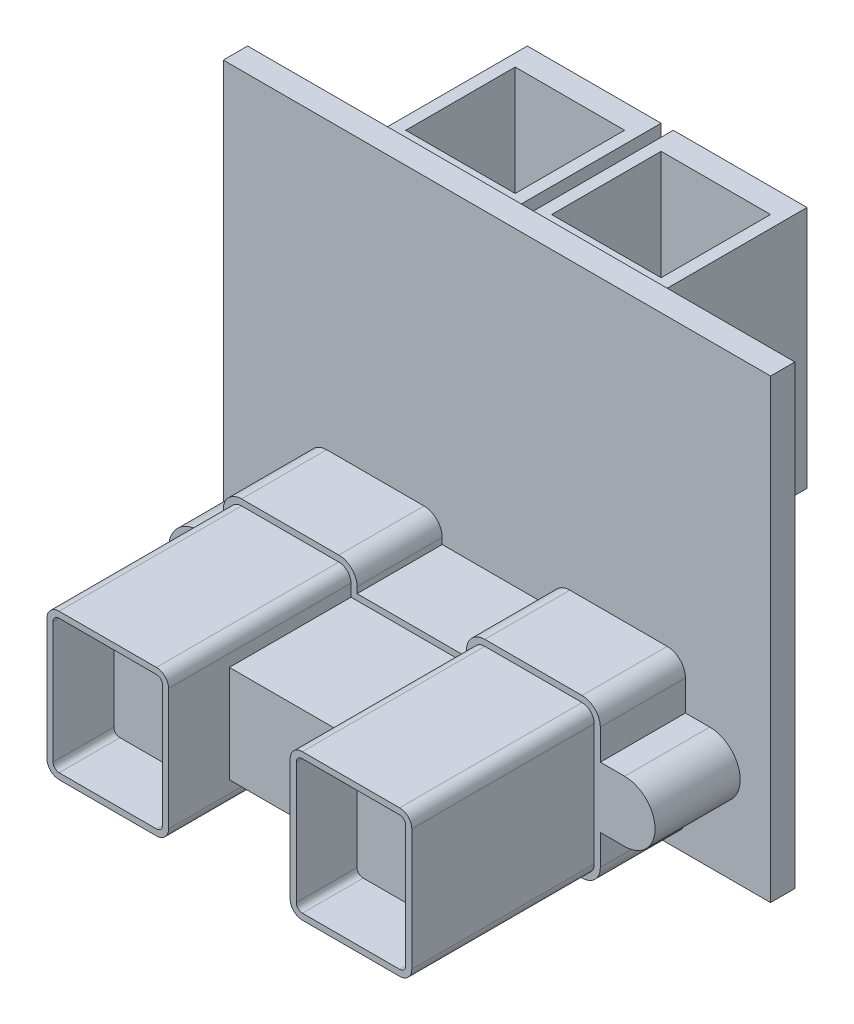
SolidWorks part; units mm, degrees
ref_plane "Front Plane" through (0, 0, 0) normal (0, 0, 1) x (1, 0, 0)
ref_plane "Top Plane" through (0, 0, 0) normal (0, 1, 0) x (1, 0, 0)
ref_plane "Right Plane" through (0, 0, 0) normal (1, 0, 0) x (0, 0, -1)
sketch "Sketch1" plane through (0, 0, 0) normal (0, 0, 1) x (1, 0, 0)
  line L1 (-22.5, 18.75) -> (22.5, 18.75)
  line L2 (-22.5, 18.75) -> (-22.5, -18.75)
  line L3 (-22.5, -18.75) -> (22.5, -18.75)
  line L4 (22.5, 18.75) -> (22.5, -18.75)
  line L5 (-22.5, 18.75) -> (22.5, -18.75) construction
  line L6 (-22.5, -18.75) -> (22.5, 18.75) construction
  point P0 (0, 0)
  dimension "D1" = 37.5
  dimension "D2" = 45
extrude "Boss-Extrude1" add sketch "Sketch1" along normal blind 2
sketch "Sketch2" plane through (0, 0, 2) normal (0, 0, 1) x (1, 0, 0)
  line L0 (0, 18.75) -> (0, -18.75) construction
  line L1 (22.5, 18.75) -> (-22.5, 18.75) construction
  line L2 (-22.5, -18.75) -> (22.5, -18.75) construction
  line L4 (-20, -4.75) -> (20, -4.75)
  line L5 (-20, -4.75) -> (-20, -17.75)
  line L6 (-20, -17.75) -> (20, -17.75)
  line L7 (20, -4.75) -> (20, -17.75)
  line L8 (-20, -4.75) -> (20, -17.75) construction
  line L9 (-20, -17.75) -> (20, -4.75) construction
  point P6 (0, -11.25)
  point P11 (0, -10.9554)
  dimension "D1" = 13
  dimension "D2" = 40
  dimension "D3" = 1
extrude "Boss-Extrude2" add sketch "Sketch2" along normal blind 7
sketch "Sketch3" plane through (0, 0, 9) normal (0, 0, 1) x (1, 0, 0)
  line L0 (0, -4.75) -> (0, -17.75) construction
  line L1 (20, -4.75) -> (-20, -4.75) construction
  line L2 (-20, -17.75) -> (20, -17.75) construction
  line L3 (-5, -7.25) -> (-5, -5.25)
  line L4 (5, -5.25) -> (15, -5.25)
  line L5 (5, -7.25) -> (5, -5.25)
  line L6 (5, -17.25) -> (15, -17.25)
  line L7 (15, -5.25) -> (15, -17.25)
  line L8 (-5, -5.25) -> (-15, -5.25)
  line L9 (5, -15.25) -> (5, -17.25)
  line L10 (-5, -17.25) -> (-15, -17.25)
  line L11 (-15, -5.25) -> (-15, -17.25)
  line L12 (5, -7.25) -> (-5, -7.25)
  line L13 (-5, -15.25) -> (-5, -17.25)
  line L14 (5, -15.25) -> (-5, -15.25)
  line L15 (-20, -17.75) -> (20, -17.75) construction
  point P20 (0, -7.25)
  point P24 (0, -15.25)
  dimension "D1" = 0.5
  dimension "D2" = 0.5
  dimension "D3" = 30
  dimension "D5" = 10
  dimension "D6" = 2
  dimension "D7" = 2
extrude "Boss-Extrude3" add sketch "Sketch3" along normal blind 15
fillet "Fillet1" radius 1 8 edges at (-15, -17.25, 16.5) (-5, -17.25, 16.5) (5, -17.25, 16.5) (-15, -5.25, 16.5) (15, -17.25, 16.5) (15, -5.25, 16.5) (5, -5.25, 16.5) (-5, -5.25, 16.5)
sketch "Sketch4" plane through (0, 0, 24) normal (0, 0, 1) x (1, 0, 0)
  line L0 (-5.5, -14.75) -> (-5.5, -7.75)
  line L1 (5.5, -7.75) -> (5.5, -14.75)
  line L2 (5, -7.25) -> (5, -15.25)
  line L3 (5, -15.25) -> (-5, -15.25)
  line L4 (-5, -15.25) -> (-5, -7.25)
  line L5 (-5, -7.25) -> (5, -7.25)
  line L48 (-14.5, -6.25) -> (-14.5, -16.25)
  line L49 (-14, -16.75) -> (-6, -16.75)
  line L50 (-5.5, -16.25) -> (-5.5, -14.75)
  line L51 (-5.5, -14.75) -> (5.5, -14.75)
  line L52 (5.5, -14.75) -> (5.5, -16.25)
  line L53 (6, -16.75) -> (14, -16.75)
  line L54 (14.5, -16.25) -> (14.5, -6.25)
  line L55 (14, -5.75) -> (6, -5.75)
  line L56 (5.5, -6.25) -> (5.5, -7.75)
  line L57 (5.5, -7.75) -> (-5.5, -7.75)
  line L58 (-5.5, -7.75) -> (-5.5, -6.25)
  line L59 (-6, -5.75) -> (-14, -5.75)
  line L60 (-14.5, -6.25) -> (-14.5, -16.25)
  line L61 (-14, -16.75) -> (-6, -16.75)
  line L62 (-5.5, -16.25) -> (-5.5, -14.75)
  line L63 (-5.5, -14.75) -> (5.5, -14.75) construction
  line L64 (5.5, -14.75) -> (5.5, -16.25)
  line L65 (6, -16.75) -> (14, -16.75)
  line L66 (14.5, -16.25) -> (14.5, -6.25)
  line L67 (14, -5.75) -> (6, -5.75)
  line L68 (5.5, -6.25) -> (5.5, -7.75)
  line L69 (5.5, -7.75) -> (-5.5, -7.75) construction
  line L70 (-5.5, -7.75) -> (-5.5, -6.25)
  line L71 (-6, -5.75) -> (-14, -5.75)
  arc A32 (-14.5, -16.25) -> (-14, -16.75) centre (-14, -16.25) ccw
  arc A33 (-6, -16.75) -> (-5.5, -16.25) centre (-6, -16.25) ccw
  arc A34 (5.5, -16.25) -> (6, -16.75) centre (6, -16.25) ccw
  arc A35 (14, -16.75) -> (14.5, -16.25) centre (14, -16.25) ccw
  arc A36 (14.5, -6.25) -> (14, -5.75) centre (14, -6.25) ccw
  arc A37 (6, -5.75) -> (5.5, -6.25) centre (6, -6.25) ccw
  arc A38 (-5.5, -6.25) -> (-6, -5.75) centre (-6, -6.25) ccw
  arc A39 (-14, -5.75) -> (-14.5, -6.25) centre (-14, -6.25) ccw
  arc A40 (-14.5, -16.25) -> (-14, -16.75) centre (-14, -16.25) ccw
  arc A41 (-6, -16.75) -> (-5.5, -16.25) centre (-6, -16.25) ccw
  arc A42 (5.5, -16.25) -> (6, -16.75) centre (6, -16.25) ccw
  arc A43 (14, -16.75) -> (14.5, -16.25) centre (14, -16.25) ccw
  arc A44 (14.5, -6.25) -> (14, -5.75) centre (14, -6.25) ccw
  arc A45 (6, -5.75) -> (5.5, -6.25) centre (6, -6.25) ccw
  arc A46 (-5.5, -6.25) -> (-6, -5.75) centre (-6, -6.25) ccw
  arc A47 (-14, -5.75) -> (-14.5, -6.25) centre (-14, -6.25) ccw
  dimension "D1" = 0.5
extrude "Cut-Extrude1" cut sketch "Sketch4" against normal blind 5
sketch "Sketch5" plane through (0, 0, 9) normal (0, 0, 1) x (1, 0, 0)
  line L11 (-20, -4.75) -> (-20, -17.75) construction
  line L12 (20, -17.75) -> (20, -4.75) construction
  line L15 (-15.5, -6.25) -> (-15.5, -16.25)
  line L16 (-14, -17.75) -> (-6, -17.75)
  line L17 (6, -17.75) -> (14, -17.75)
  line L18 (-4.5, -15.75) -> (4.5, -15.75)
  line L19 (-4.5, -16.25) -> (-4.5, -15.75)
  line L20 (4.5, -15.75) -> (4.5, -16.25)
  line L21 (-14, -17.75) -> (-6, -17.75)
  line L22 (6, -17.75) -> (14, -17.75)
  line L23 (-4.5, -15.75) -> (4.5, -15.75)
  line L24 (-4.5, -16.25) -> (-4.5, -15.75)
  line L25 (4.5, -15.75) -> (4.5, -16.25)
  line L26 (-15.5, -6.25) -> (-15.5, -16.25) construction
  line L27 (-17.5, -8.75) -> (-15.5, -8.75)
  line L28 (15.5, -16.25) -> (15.5, -6.25)
  line L29 (15.5, -16.25) -> (15.5, -6.25) construction
  line L30 (-15.5, -8.75) -> (-15.5, -6.25)
  line L31 (-17.5, -13.75) -> (-15.5, -13.75)
  line L32 (-15.5, -13.75) -> (-15.5, -16.25)
  line L33 (17.5, -13.75) -> (15.5, -13.75)
  line L34 (15.5, -13.75) -> (15.5, -16.25)
  line L35 (17.5, -8.75) -> (15.5, -8.75)
  line L36 (15.5, -8.75) -> (15.5, -6.25)
  line L51 (20.5, -18.25) -> (20.5, -4.25)
  line L52 (-20.5, -18.25) -> (20.5, -18.25)
  line L53 (-20.5, -4.25) -> (-20.5, -18.25)
  line L54 (20.5, -4.25) -> (-20.5, -4.25)
  line L55 (20.5, -18.25) -> (20.5, -4.25)
  line L56 (-20.5, -18.25) -> (20.5, -18.25)
  line L57 (-20.5, -4.25) -> (-20.5, -18.25)
  line L58 (20.5, -4.25) -> (-20.5, -4.25)
  line L214 (14, -4.75) -> (6, -4.75)
  line L215 (4.5, -6.25) -> (4.5, -6.75)
  line L216 (4.5, -6.75) -> (-4.5, -6.75)
  line L217 (-4.5, -6.75) -> (-4.5, -6.25)
  line L218 (-6, -4.75) -> (-14, -4.75)
  line L219 (14, -4.75) -> (6, -4.75)
  line L220 (4.5, -6.25) -> (4.5, -6.75)
  line L221 (4.5, -6.75) -> (-4.5, -6.75)
  line L222 (-4.5, -6.75) -> (-4.5, -6.25)
  line L223 (-6, -4.75) -> (-14, -4.75)
  circle A4 centre (-17.5, -11.25) radius 2.5 construction
  circle A5 centre (17.5, -11.25) radius 2.5 construction
  arc A6 (-6, -17.75) -> (-4.5, -16.25) centre (-6, -16.25) ccw
  arc A7 (4.5, -16.25) -> (6, -17.75) centre (6, -16.25) ccw
  arc A8 (-6, -17.75) -> (-4.5, -16.25) centre (-6, -16.25) ccw
  arc A9 (4.5, -16.25) -> (6, -17.75) centre (6, -16.25) ccw
  arc A14 (-15.5, -16.25) -> (-14, -17.75) centre (-14, -16.25) ccw
  arc A15 (-14, -4.75) -> (-15.5, -6.25) centre (-14, -6.25) ccw
  arc A16 (-15.5, -16.25) -> (-14, -17.75) centre (-14, -16.25) ccw
  arc A17 (-14, -4.75) -> (-15.5, -6.25) centre (-14, -6.25) ccw
  arc A18 (-17.5, -13.75) -> (-17.5, -8.75) centre (-17.5, -11.25) cw
  arc A19 (17.5, -8.75) -> (17.5, -13.75) centre (17.5, -11.25) cw
  arc A20 (14, -17.75) -> (15.5, -16.25) centre (14, -16.25) ccw
  arc A21 (15.5, -6.25) -> (14, -4.75) centre (14, -6.25) ccw
  arc A22 (14, -17.75) -> (15.5, -16.25) centre (14, -16.25) ccw
  arc A23 (15.5, -6.25) -> (14, -4.75) centre (14, -6.25) ccw
  arc A85 (6, -4.75) -> (4.5, -6.25) centre (6, -6.25) ccw
  arc A86 (-4.5, -6.25) -> (-6, -4.75) centre (-6, -6.25) ccw
  arc A87 (6, -4.75) -> (4.5, -6.25) centre (6, -6.25) ccw
  arc A88 (-4.5, -6.25) -> (-6, -4.75) centre (-6, -6.25) ccw
  point P13 (-20, -11.25)
  dimension "D3" = 5
  dimension "D1" = 0.5
  dimension "D2" = 0.5
  dimension "D4" = 0.5
  dimension "D5" = 0.5
  dimension "D6" = 0.5
extrude "Cut-Extrude2" cut sketch "Sketch5" against normal up to surface (7 mm away) up to face at (0, 0, 2)
sketch "Sketch6" plane through (0, 0, 0) normal (0, 0, -1) x (-1, 0, 0)
  line L0 (0, 18.75) -> (0, -18.75) construction
  line L1 (-22.5, 18.75) -> (22.5, 18.75) construction
  line L2 (22.5, -18.75) -> (-22.5, -18.75) construction
  line L3 (-0.5, 18.25) -> (-0.5, -1.75)
  line L4 (-11.5, 18.25) -> (11.5, 18.25) construction
  line L5 (-11.5, 18.25) -> (-11.5, -1.75)
  line L6 (-11.5, -1.75) -> (11.5, -1.75) construction
  line L7 (11.5, 18.25) -> (11.5, -1.75)
  line L8 (-11.5, 18.25) -> (11.5, -1.75) construction
  line L9 (-11.5, -1.75) -> (11.5, 18.25) construction
  line L10 (-0.5, -1.75) -> (-11.5, -1.75)
  line L11 (-11.5, 18.25) -> (-0.5, 18.25)
  line L12 (11.5, 18.25) -> (0.5, 18.25)
  line L13 (0.5, 18.25) -> (0.5, -1.75)
  line L14 (0.5, -1.75) -> (11.5, -1.75)
  point P6 (0, 8.25)
  dimension "D1" = 20
  dimension "D2" = 23
  dimension "D3" = 11
  dimension "D4" = 0.5
extrude "Boss-Extrude5" add sketch "Sketch6" along normal blind 12
sketch "Sketch7" plane through (0, 18.25, 0) normal (0, 1, 0) x (1, 0, 0)
  line L0 (-11.5, 12) -> (-0.5, 12) construction
  line L1 (-10.5, 10) -> (-1.5, 10)
  line L2 (-10.5, 10) -> (-10.5, 1)
  line L3 (-10.5, 1) -> (-1.5, 1)
  line L4 (-1.5, 10) -> (-1.5, 1)
  line L5 (1.5, 10) -> (10.5, 10)
  line L6 (1.5, 10) -> (1.5, 1)
  line L7 (1.5, 1) -> (10.5, 1)
  line L8 (10.5, 10) -> (10.5, 1)
  line L9 (-11.5, 12) -> (-11.5, 0) construction
  line L10 (-0.5, 12) -> (-0.5, 0) construction
  line L11 (0.5, 12) -> (0.5, 0) construction
  line L12 (0.5, 0) -> (11.5, 0) construction
  dimension "D1" = 2
  dimension "D2" = 1
  dimension "D3" = 1
  dimension "D4" = 1
  dimension "D5" = 1
extrude "Cut-Extrude3" cut sketch "Sketch7" against normal blind 12
